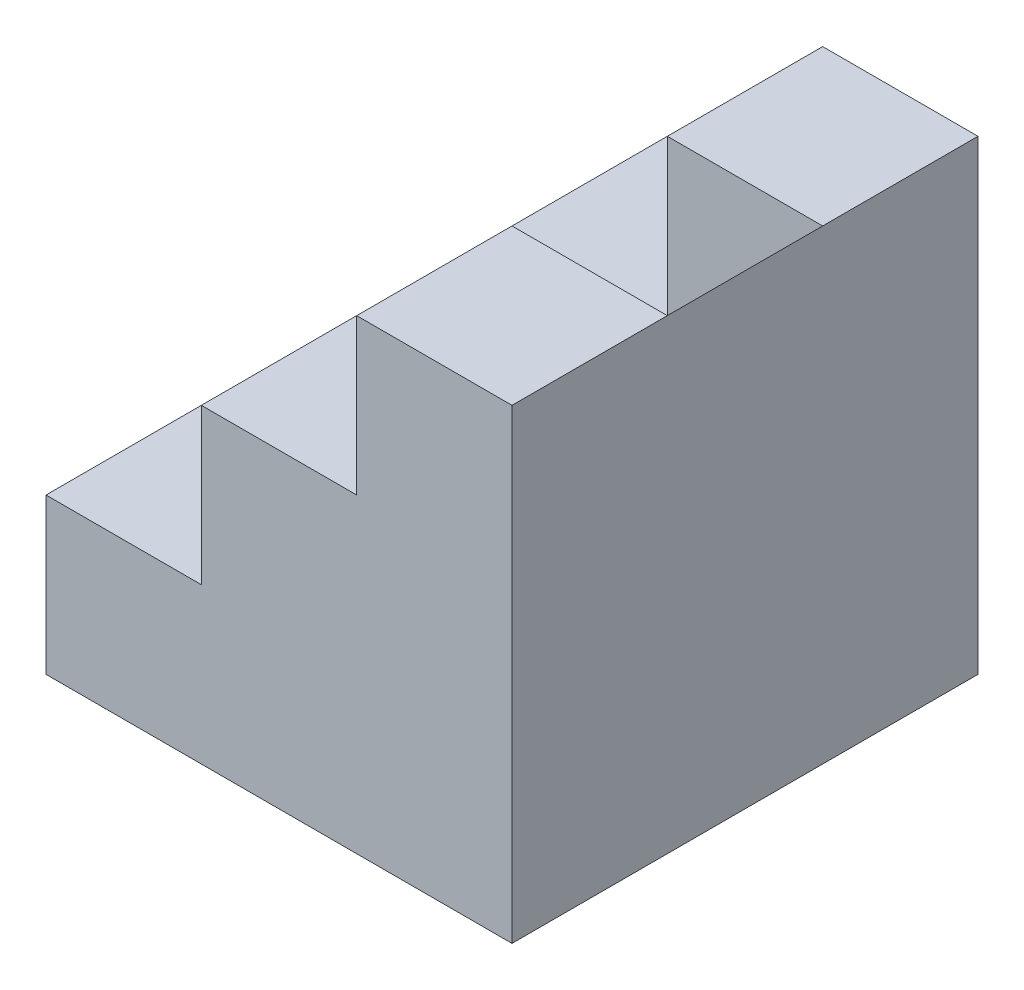
SolidWorks part; units mm, degrees
ref_plane "Alzado" through (0, 0, 0) normal (0, 0, 1) x (1, 0, 0)
ref_plane "Planta" through (0, 0, 0) normal (0, 1, 0) x (1, 0, 0)
ref_plane "Vista lateral" through (0, 0, 0) normal (1, 0, 0) x (0, 0, -1)
sketch "Croquis1" plane through (0, 0, 0) normal (0, 0, 1) x (1, 0, 0)
  line L0 (0, 0) -> (-60, 0)
  line L7 (0, 60) -> (0, 0)
  line L8 (-60, 0) -> (-60, 60)
  line L9 (-60, 60) -> (0, 60)
  dimension "D1" = 60
  dimension "D3" = 60
extrude "Saliente-Extruir2" add sketch "Croquis1" against normal blind 60
sketch "Croquis13" plane through (0, 0, 0) normal (0, 0, 1) x (1, 0, 0)
  line L0 (-60, 0) -> (-60, 20)
  line L1 (-60, 60) -> (-60, 0) construction
  line L2 (-60, 20) -> (-40, 20)
  line L3 (-40, 20) -> (-40, 40)
  line L4 (-40, 40) -> (-20, 40)
  line L5 (-20, 40) -> (-20, 60)
  line L6 (0, 60) -> (-60, 60) construction
  line L7 (-20, 60) -> (0, 60)
  line L8 (0, 60) -> (0, 0)
  line L9 (0, 0) -> (-60, 0)
  line L10 (-60, 20) -> (-60, 40)
  line L11 (-60, 40) -> (-40, 40)
  line L12 (-60, 40) -> (-60, 60)
  line L13 (-60, 60) -> (-20, 60)
  dimension "D1" = 20
  dimension "D2" = 20
  dimension "D3" = 20
  dimension "D4" = 20
extrude "Cortar-Extruir15" cut sketch "Croquis13" against normal blind 20 contours L3 L11 L4 L5 L1 | L11 L3 L2
sketch "Croquis17" plane through (0, 0, -60) normal (0, 0, -1) x (-1, 0, 0)
  line L0 (0, 60) -> (20, 60)
  line L1 (0, 60) -> (60, 60) construction
  line L2 (20, 60) -> (20, 40)
  line L3 (20, 40) -> (40, 40)
  line L4 (40, 40) -> (40, 20)
  line L5 (40, 20) -> (60, 20)
  line L6 (60, 60) -> (60, 0) construction
  line L7 (60, 20) -> (60, 60)
  line L8 (60, 60) -> (20, 60)
  line M9 (60, 0) -> (60, 60)
  line M10 (60, 60) -> (0, 60)
  dimension "D1" = 20
  dimension "D2" = 20
  dimension "D3" = 20
  dimension "D4" = 20
extrude "Cortar-Extruir17" cut sketch "Croquis17" against normal blind 20 contours L4 L5 L2 L3 M9 M10
sketch "Croquis20" plane through (0, 60, 0) normal (0, 1, 0) x (1, 0, 0)
  line L0 (-60, 40) -> (0, 40)
  line L1 (0, 60) -> (0, 0) construction
  line L2 (-60, 20) -> (0, 20)
  line L3 (-60, 40) -> (-60, 20)
  line L4 (0, 20) -> (0, 40)
extrude "Cortar-Extruir19" cut sketch "Croquis20" against normal through all
sketch "Croquis21" plane through (0, 0, -40) normal (0, 0, 1) x (1, 0, 0)
  line L0 (0, 60) -> (-60, 0)
  line L1 (0, 0) -> (-60, 0) construction
  line L2 (-60, 0) -> (0, 0)
  line L3 (0, 0) -> (0, 60)
extrude "Saliente-Extruir3" add sketch "Croquis21" along normal up to next
